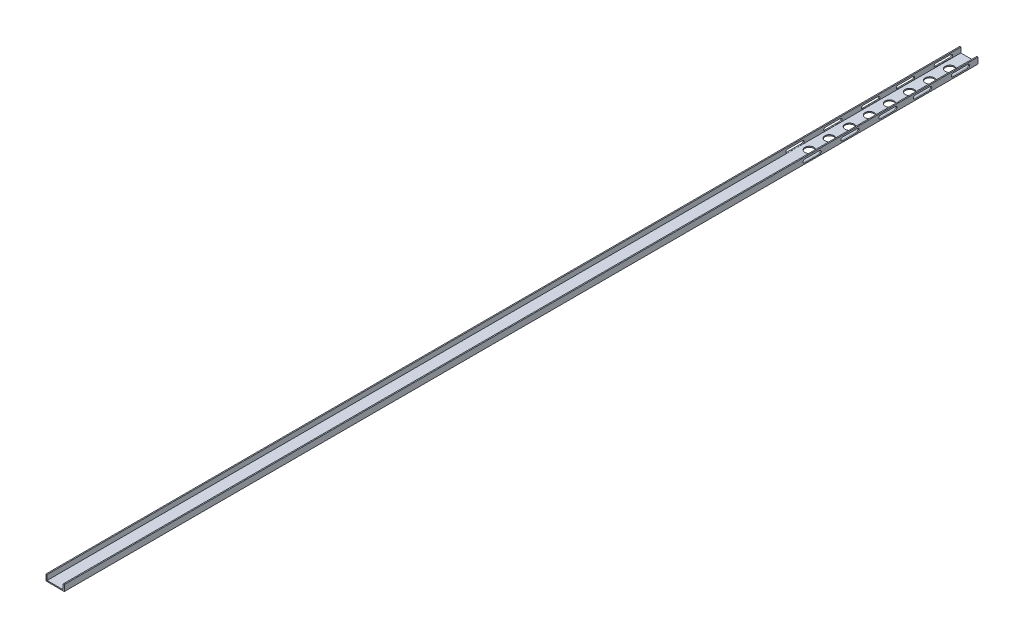
SolidWorks part; units mm, degrees
ref_plane "Front Plane" through (0, 0, 0) normal (0, 0, 1) x (1, 0, 0)
ref_plane "Top Plane" through (0, 0, 0) normal (0, 1, 0) x (1, 0, 0)
ref_plane "Right Plane" through (0, 0, 0) normal (1, 0, 0) x (0, 0, -1)
sketch "Sketch1" plane through (0, 0, 0) normal (0, 0, 1) x (1, 0, 0)
  line L0 (-11.2273, -5.2873) -> (10.7727, -5.2873)
  line L1 (-11.2273, -5.2873) -> (-11.2273, 1.7127)
  line L2 (12.2727, -6.6873) -> (-12.7273, -6.6873)
  line L3 (-12.7273, -6.6873) -> (-12.7273, 1.7127)
  line L4 (-12.7273, 1.7127) -> (-11.2273, 1.7127)
  line L5 (12.2727, -6.6873) -> (12.2727, 1.7127)
  line L6 (12.2727, 1.7127) -> (10.7727, 1.7127)
  line L7 (10.7727, 1.7127) -> (10.7727, -5.2873)
  dimension "D2" = 25
  dimension "D3" = 1.5
  dimension "D4" = 8.4
  dimension "D5" = 8.4
  dimension "D6" = 1.5
  dimension "D7" = 1.5
  dimension "D8" = 1.4
extrude "Boss-Extrude1" add sketch "Sketch1" along normal blind 1247.2781 and the other way blind 0.0001
sketch "Sketch6" plane through (0, -5.2873, 0) normal (0, 1, 0) x (1, 0, 0)
  line L0 (0, 0) -> (-0.2273, -1247.2781) construction
  line L1 (10.7727, -1247.2781) -> (-11.2273, -1247.2781) construction
  circle A0 centre (-0.0036, -20) radius 5
  circle A1 centre (-0.0086, -47.375) radius 5
  circle A2 centre (-0.0136, -74.75) radius 5
  circle A3 centre (-0.0186, -102.125) radius 5
  circle A4 centre (-0.0236, -129.5) radius 5
  circle A5 centre (-0.0286, -156.875) radius 5
  circle A6 centre (-0.0336, -184.25) radius 5
  circle A7 centre (-0.0386, -211.625) radius 5
  dimension "D9" = 20
  dimension "D1" = 27.375
  dimension "D2" = 1247.2781
  dimension "D3" = 27.375
  dimension "D4" = 27.375
  dimension "D5" = 27.375
  dimension "D6" = 27.375
  dimension "D7" = 27.375
  dimension "D8" = 27.375
extrude "Cut-Extrude1" [suppressed] cut sketch "Sketch6" against normal through all
hole_wizard "CBORE for M5 Hex Head Bolt1" positions "Sketch10" profile "Sketch11" counterbore size "M5" standard "BSI" end condition through all
sketch "Sketch10" plane through (0, -5.2873, 0) normal (0, 1, 0) x (1, 0, 0)
  point P2 (0, -26.2266)
  point P4 (0, -53.6016)
  point P6 (0, -80.9766)
  point P8 (0, -108.3516)
  point P10 (0, -135.7266)
  point P12 (0, -163.1016)
  point P14 (0, -190.4766)
  point P16 (0, -217.8516)
  dimension "D2" = 27.375
  dimension "D3" = 27.375
  dimension "D4" = 27.375
  dimension "D5" = 27.375
  dimension "D6" = 27.375
  dimension "D7" = 27.375
sketch "Sketch11" plane through (0, -5.2873, 26.2266) normal (1, 0, 0) x (0, 0, 1)
  line L0 (0, 0) -> (0, 1.4)
  line L1 (0, 1.4) -> (2.9, 1.4)
  line L3 (2.9, 1.4) -> (2.9, 3.5)
  line L4 (2.9, 3.5) -> (6.119, 3.5)
  line L5 (6.119, 3.5) -> (6.119, 0)
  line L7 (6.119, 0) -> (0, 0)
  line L11 (0, -6.35) -> (0, 107.95) construction
  dimension "Thru Hole Dia." = 5.8
  dimension "Thru Hole Depth" = 1.4
  dimension "C'Bore Dia." = 12.238
  dimension "C'Bore Depth" = 3.5
sketch "Sketch12" plane through (-12.7273, 0, 0) normal (-1, 0, 0) x (0, 0, 1)
  line L0 (13.5434, -0.3504) -> (34.1824, -0.3504)
  line L1 (13.5434, -4.7356) -> (34.1824, -4.7356)
  line L2 (13.5434, -0.3504) -> (13.5434, -4.7356)
  line L3 (34.1824, -0.3504) -> (34.1824, -4.7356)
  line L4 (65.3052, -0.5178) -> (85.9324, -0.5178)
  line L5 (65.3052, -4.9029) -> (85.9324, -4.9029)
  line L6 (65.3052, -0.5178) -> (65.3052, -4.9029)
  line L7 (85.9324, -0.5178) -> (85.9324, -4.9029)
  line L8 (-0.0001, -2.4873) -> (1247.2781, -2.4873) construction
  line L9 (-0.0001, 1.7127) -> (-0.0001, -6.6873) construction
  line L10 (1247.2781, 1.7127) -> (1247.2781, -6.6873) construction
  line L11 (112.7032, -0.4476) -> (133.3304, -0.4476)
  line L12 (112.7032, -4.8327) -> (133.3304, -4.8327)
  line L13 (112.7032, -0.4476) -> (112.7032, -4.8327)
  line L14 (133.3304, -0.4476) -> (133.3304, -4.8327)
  line L15 (164.346, -0.6112) -> (184.9732, -0.6112)
  line L16 (164.346, -4.9964) -> (184.9732, -4.9964)
  line L17 (164.346, -0.6112) -> (164.346, -4.9964)
  line L18 (184.9732, -0.6112) -> (184.9732, -4.9964)
  line L19 (216.1078, -0.7786) -> (236.7351, -0.7786)
  line L20 (216.1078, -5.1637) -> (236.7351, -5.1637)
  line L21 (216.1078, -0.7786) -> (216.1078, -5.1637)
  line L22 (236.7351, -0.7786) -> (236.7351, -5.1637)
  circle A0 centre (13.5434, -2.543) radius 2.1926
  circle A2 centre (34.1824, -2.543) radius 2.1982
  circle A3 centre (65.3052, -2.7104) radius 2.1926
  circle A4 centre (85.9324, -2.7104) radius 2.1786
  circle A5 centre (112.7032, -2.6402) radius 2.1926
  circle A6 centre (133.3304, -2.6402) radius 2.1826
  circle A7 centre (164.346, -2.8038) radius 2.1926
  circle A8 centre (184.9732, -2.8038) radius 2.1911
  circle A9 centre (216.1078, -2.9712) radius 2.1926
  circle A10 centre (236.7351, -2.9712) radius 2.1841
extrude "Cut-Extrude3" cut sketch "Sketch12" against normal blind 219 contours L14 L8 A6 L11 | L8 L14 L12 A6 | L8 A5 L12 A6 | A5 L8 A6 L11 | L19 L22 L20 L21 | A10 | A9 | A8 | L16 L18 L15 L17 | A7 | A3 | L4 L7 L5 L6 | A4 | L0 L3 L1 L2 | A2 | A0
scale "Scale1" bodies to scale 107 scale about origin uniform scaling yes scale factor 1.8
